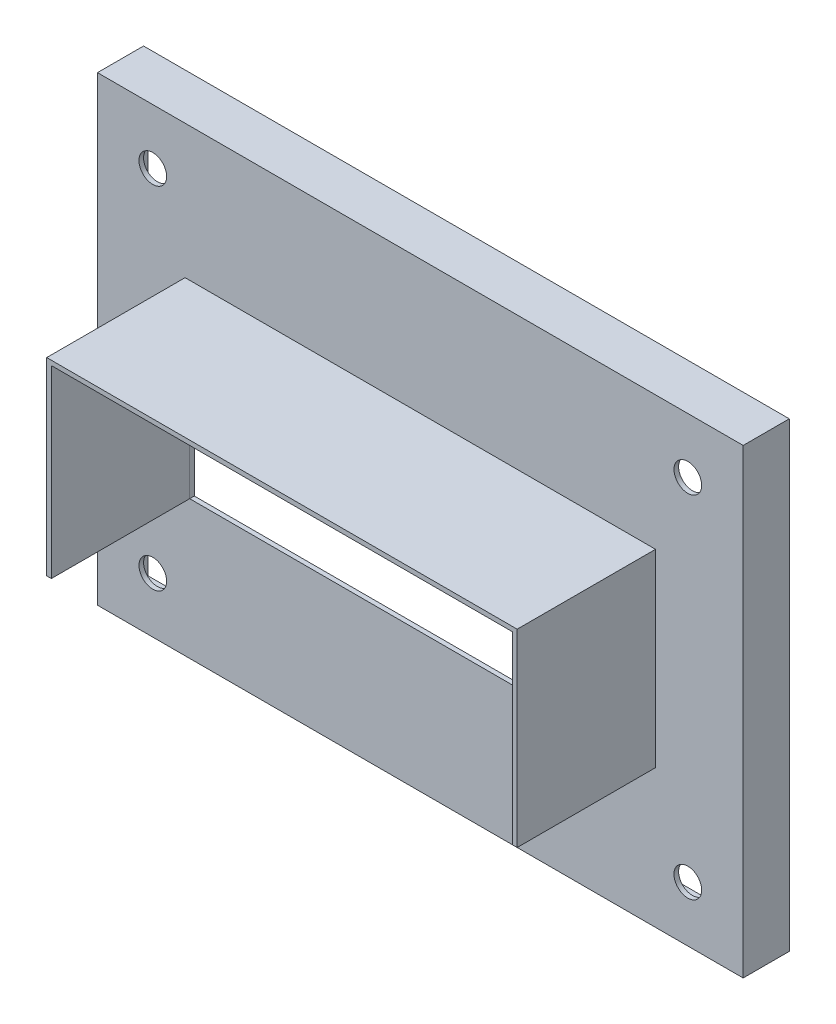
SolidWorks part; units mm, degrees
ref_plane "Alzado" through (0, 0, 0) normal (0, 0, 1) x (1, 0, 0)
ref_plane "Planta" through (0, 0, 0) normal (0, 1, 0) x (1, 0, 0)
ref_plane "Vista lateral" through (0, 0, 0) normal (1, 0, 0) x (0, 0, -1)
sketch "Croquis1" plane through (0, 0, 0) normal (0, 0, 1) x (1, 0, 0)
  line L0 (-69, 49) -> (69, 49)
  line L1 (-70, -50) -> (70, -50)
  line L2 (-70, -50) -> (-70, 50)
  line L3 (-70, 50) -> (70, 50)
  line L4 (70, -50) -> (70, 50)
  line L5 (-70, -50) -> (70, 50) construction
  line L6 (-70, 50) -> (70, -50) construction
  line L7 (69, -49) -> (69, 49)
  line L8 (-69, -49) -> (69, -49)
  line L9 (-69, -49) -> (-69, 49)
  point P0 (0, 0)
  dimension "D1" = 140
  dimension "D2" = 100
  dimension "D3" = 1
extrude "Saliente-Extruir1" add sketch "Croquis1" against normal blind 10
sketch "Croquis2" plane through (0, 0, 0) normal (0, 0, 1) x (1, 0, 0)
  line L1 (-69, -49) -> (69, -49)
  line L2 (-69, -49) -> (-69, 49)
  line L3 (-69, 49) -> (69, 49)
  line L4 (69, -49) -> (69, 49)
  line L5 (-69, -49) -> (69, 49) construction
  line L6 (-69, 49) -> (69, -49) construction
  point P0 (0, 0)
extrude "Saliente-Extruir2" add sketch "Croquis2" against normal blind 1
sketch "Croquis4" plane through (0, 0, 0) normal (0, 0, 1) x (1, 0, 0)
  line L0 (-70, 50) -> (-70, -50) construction
  line L1 (0, -5.5) -> (0, 5.5) construction
  line L2 (70, 50) -> (-70, 50) construction
  line L4 (5.5, 0) -> (-5.5, 0) construction
  line L7 (-50, -20) -> (50, -20)
  line L8 (-50, -20) -> (-50, 20)
  line L9 (-50, 20) -> (50, 20)
  line L10 (50, -20) -> (50, 20)
  line L11 (-50, -20) -> (50, 20) construction
  line L12 (-50, 20) -> (50, -20) construction
  circle A1 centre (-58, 38) radius 3
  circle A2 centre (58, 38) radius 3
  circle A3 centre (58, -38) radius 3
  circle A4 centre (-58, -38) radius 3
  point P19 (0, 0)
  dimension "D1" = 12
  dimension "D2" = 12
  dimension "D3" = 100
  dimension "D4" = 40
extrude "Cortar-Extruir1" cut sketch "Croquis4" against normal blind 1
sketch "Croquis5" plane through (0, 0, 0) normal (0, 0, 1) x (1, 0, 0)
  line L0 (-50, -20) -> (-50, 20)
  line L1 (-50, 20) -> (50, 20)
  line L2 (50, 20) -> (50, -20)
  line L3 (-51, -20) -> (-51, 21)
  line L4 (-51, 21) -> (51, 21)
  line L5 (51, 21) -> (51, -20)
  line L6 (-51, -20) -> (-50, -20)
  line L7 (51, -20) -> (50, -20)
  dimension "D1" = 1
extrude "Saliente-Extruir3" add sketch "Croquis5" along normal blind 30 separate body
